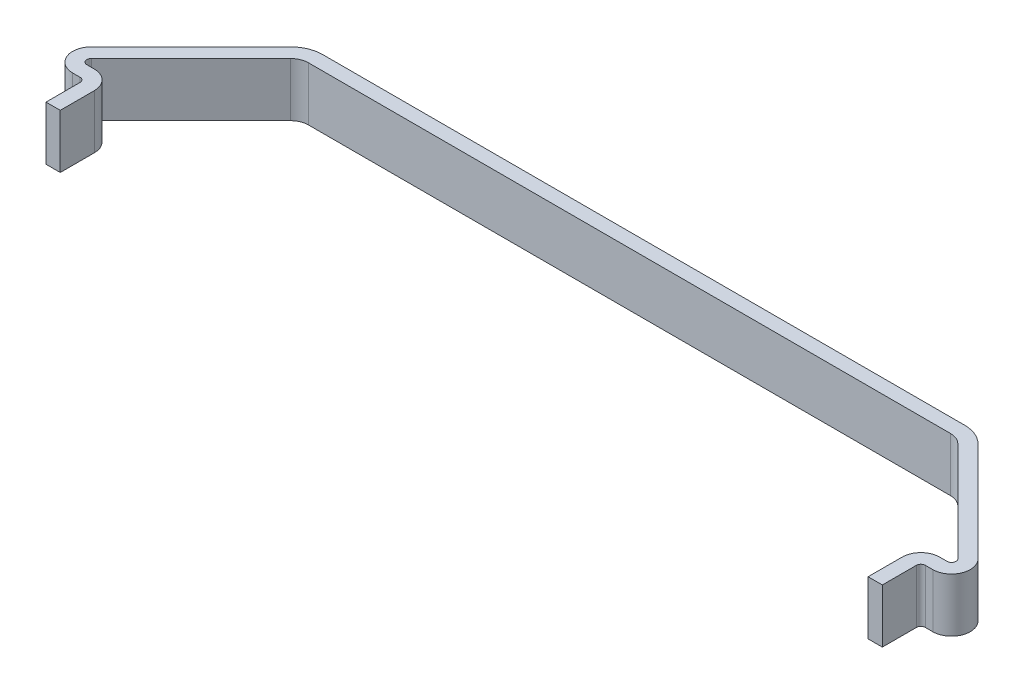
SolidWorks part; units mm, degrees
ref_plane "Front Plane" through (0, 0, 0) normal (0, 0, 1) x (1, 0, 0)
ref_plane "Top Plane" through (0, 0, 0) normal (0, 1, 0) x (1, 0, 0)
ref_plane "Right Plane" through (0, 0, 0) normal (1, 0, 0) x (0, 0, -1)
sketch "Sketch1" plane through (0, 0, 0) normal (0, 1, 0) x (1, 0, 0)
  line L0 (0, 0) -> (0, 50000) construction
  line L1 (-25, -12.5) -> (25, -12.5) construction
  line L2 (-25, -12.5) -> (-25, 12.5) construction
  line L3 (-25, 12.5) -> (25, 12.5) construction
  line L4 (25, -12.5) -> (25, 12.5) construction
  line L5 (-25, -12.5) -> (25, 12.5) construction
  line L6 (-25, 12.5) -> (25, -12.5) construction
  line L7 (17.8795, 11.7063) -> (-17.8795, 11.7062)
  line L8 (-18.5866, 11.4134) -> (-24.133, 5.867)
  line L9 (-23.9562, 5.4402) -> (-23.5437, 5.4402)
  line L10 (-22.5, 4.3964) -> (-22.5, 2.5)
  line L11 (-19.1479, 11.9746) -> (-24.6943, 6.4282)
  line L12 (-23.2937, 4.3964) -> (-23.2937, 2.5)
  line L13 (-23.2937, 2.5) -> (-22.5, 2.5)
  line L14 (-23.9562, 4.6464) -> (-23.5437, 4.6464)
  line L15 (-17.8795, 12.5) -> (17.8795, 12.5)
  line L17 (19.1479, 11.9746) -> (24.6943, 6.4282)
  line L18 (23.9562, 4.6464) -> (23.5437, 4.6464)
  line L19 (23.2937, 4.3964) -> (23.2937, 2.5)
  line L20 (23.2937, 2.5) -> (22.5, 2.5)
  line L21 (22.5, 4.3964) -> (22.5, 2.5)
  line L22 (23.9562, 5.4402) -> (23.5437, 5.4402)
  line L23 (18.5866, 11.4134) -> (24.133, 5.867)
  arc A0 (-17.8795, 11.7062) -> (-18.5866, 11.4134) centre (-17.8795, 10.7063) ccw
  arc A1 (-24.133, 5.867) -> (-23.9562, 5.4402) centre (-23.9562, 5.6902) ccw
  arc A2 (-23.5437, 5.4402) -> (-22.5, 4.3964) centre (-23.5437, 4.3964) cw
  arc A3 (-17.8795, 12.5) -> (-19.1479, 11.9746) centre (-17.8795, 10.7063) ccw
  arc A4 (-23.9562, 4.6464) -> (-24.6943, 6.4282) centre (-23.9562, 5.6902) cw
  arc A5 (-23.5437, 4.6464) -> (-23.2937, 4.3964) centre (-23.5437, 4.3964) cw
  arc A6 (17.8795, 12.5) -> (19.1479, 11.9746) centre (17.8795, 10.7063) cw
  arc A7 (23.9562, 4.6464) -> (24.6943, 6.4282) centre (23.9562, 5.6902) ccw
  arc A8 (23.5437, 4.6464) -> (23.2937, 4.3964) centre (23.5437, 4.3964) ccw
  arc A9 (23.5437, 5.4402) -> (22.5, 4.3964) centre (23.5437, 4.3964) ccw
  arc A10 (24.133, 5.867) -> (23.9562, 5.4402) centre (23.9562, 5.6902) cw
  arc A11 (17.8795, 11.7063) -> (18.5866, 11.4134) centre (17.8795, 10.7063) cw
  point P0 (0, 0)
  point P39 (-22.5, 7.5)
  dimension "D7" = 1
  dimension "D8" = 0.25
  dimension "D9" = 5
  dimension "D1" = 50
  dimension "D2" = 25
  dimension "D3" = 0.7937
  dimension "D4" = 45
  dimension "D5" = 2.5
  dimension "D6" = 15
extrude "Boss-Extrude1" add sketch "Sketch1" along normal mid plane 3
